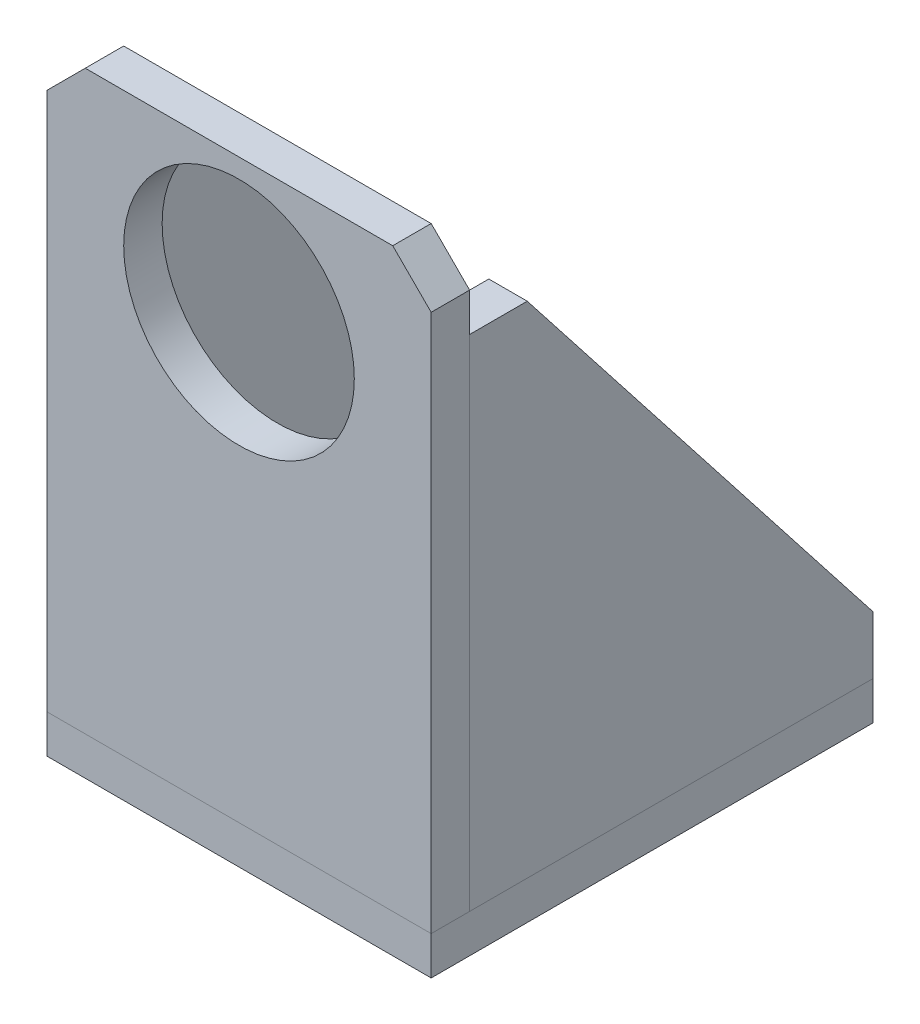
SolidWorks part; units mm, degrees
ref_plane "Plano frontal" through (0, 0, 0) normal (0, 0, 1) x (1, 0, 0)
ref_plane "Plano superior" through (0, 0, 0) normal (0, 1, 0) x (1, 0, 0)
ref_plane "Plano direito" through (0, 0, 0) normal (1, 0, 0) x (0, 0, -1)
sketch "Sketch1" plane through (0, 0, 0) normal (0, 0, 1) x (1, 0, 0)
  line L1 (-50, 0) -> (50, 0)
  line L2 (-50, 0) -> (-50, 150)
  line L3 (-50, 150) -> (50, 150)
  line L4 (50, 0) -> (50, 150)
  line L5 (0, 150) -> (0, 0) construction
  line L6 (-50, 75) -> (50, 75) construction
  point P272 (0, 75)
  dimension "D1" = 100
  dimension "D2" = 150
extrude "Boss-Extrude1" add sketch "Sketch1" along normal blind 10
sketch "Sketch3" plane through (0, 0, 0) normal (0, -1, 0) x (1, 0, 0)
  line L0 (-50, 10) -> (-50, 0) construction
  line L1 (50, 10) -> (-50, 10)
  line L2 (50, 10) -> (50, -105)
  line L3 (50, -105) -> (-50, -105)
  line L4 (-50, 10) -> (-50, -105)
  line L5 (0, -105) -> (0, 10) construction
  line L6 (50, -47.5) -> (-50, -47.5) construction
  point P244 (0, -47.5)
  dimension "D1" = 115
extrude "Boss-Extrude3" add sketch "Sketch3" along normal blind 10 separate body
sketch "Sketch4" plane through (50, 0, 0) normal (1, 0, 0) x (0, 0, -1)
  line L0 (0, 0) -> (0, 150) construction
  line L1 (105, 0) -> (0, 0)
  line L2 (0, 0) -> (0, 130)
  line L3 (0, 130) -> (15, 130)
  line L4 (15, 130) -> (105, 15)
  line L5 (105, 15) -> (105, 0)
  dimension "D1" = 15
  dimension "D2" = 15
  dimension "D3" = 20
extrude "Boss-Extrude4" add sketch "Sketch4" against normal blind 10 separate body
sketch "Sketch5" plane through (-50, 0, 0) normal (-1, 0, 0) x (0, 0, 1)
  line L3 (0, 0) -> (0, 130)
  line L4 (-105, 0) -> (0, 0)
  line L5 (0, 130) -> (-15, 130)
  line L6 (0, 0) -> (0, 130)
  line L7 (-105, 0) -> (0, 0)
  line L8 (0, 130) -> (-15, 130)
  line L11 (-105, 15) -> (-105, 0)
  line L12 (-105, 15) -> (-105, 0)
  line L13 (-15, 130) -> (-105, 15)
  line L14 (-15, 130) -> (-105, 15)
  dimension "D1" = 0
extrude "Boss-Extrude5" add sketch "Sketch5" against normal blind 10 separate body
chamfer "Chamfer1" distance 10 angle 45 2 edges at (-50, 150, 5) (50, 150, 5)
sketch "Sketch6" plane through (0, 0, 10) normal (0, 0, 1) x (1, 0, 0)
  line L0 (50, -10) -> (-50, -10) construction
  line L1 (0, 115) -> (0, 0) construction
  circle A0 centre (0, 115) radius 30
  dimension "D1" = 125
  dimension "D2" = 60
extrude "Cut-Extrude1" cut sketch "Sketch6" against normal blind 50
